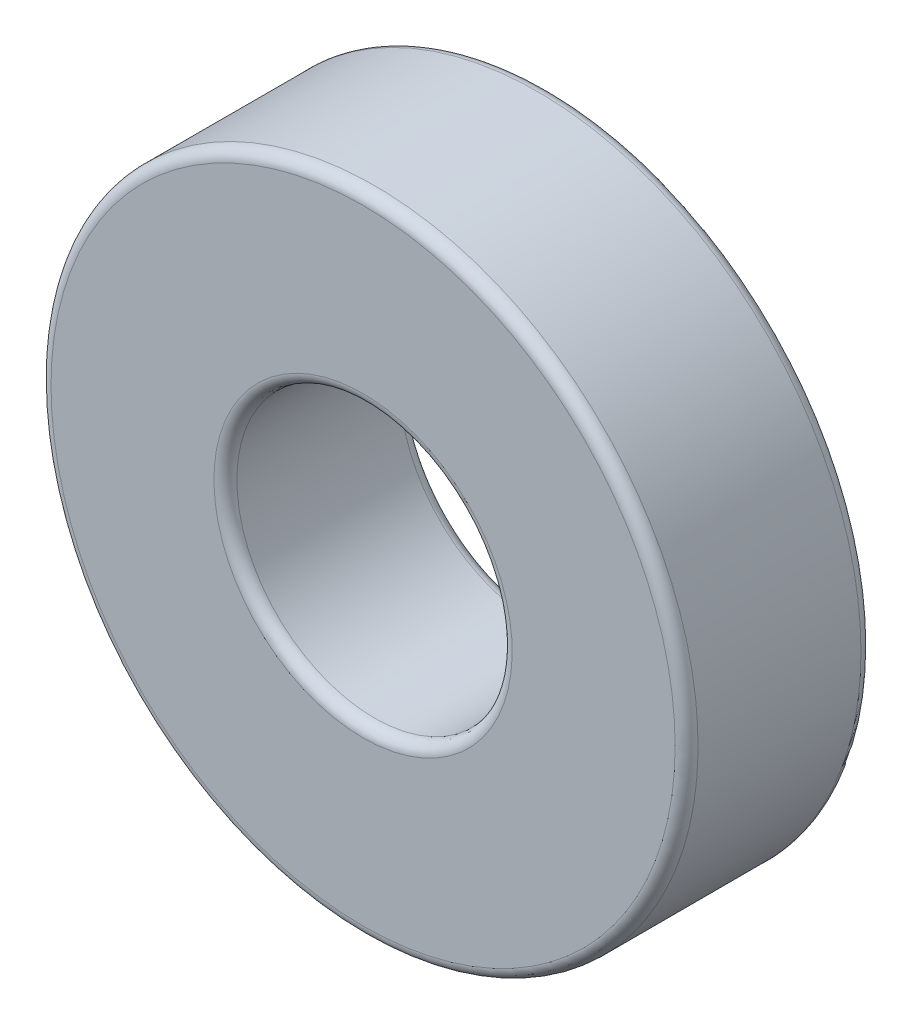
SolidWorks part; units mm, degrees
ref_plane "Front Plane" through (0, 0, 0) normal (0, 0, 1) x (1, 0, 0)
ref_plane "Top Plane" through (0, 0, 0) normal (0, 1, 0) x (1, 0, 0)
ref_plane "Right Plane" through (0, 0, 0) normal (1, 0, 0) x (0, 0, -1)
sketch "Sketch1" plane through (0, 0, 0) normal (0, 0, 1) x (1, 0, 0)
  circle A1 centre (1.9595, 0) radius 6
  circle A2 centre (1.9595, 0) radius 14.1
extrude "Boss-Extrude1" add sketch "Sketch1" along normal up to surface (8.1 mm away)
fillet "Fillet1" radius 0.5 4 edges at (16.0595, 0, 0) (7.9595, 0, 0) (1.9595, -14.1, 8.1) (1.9595, -6, 8.1)
